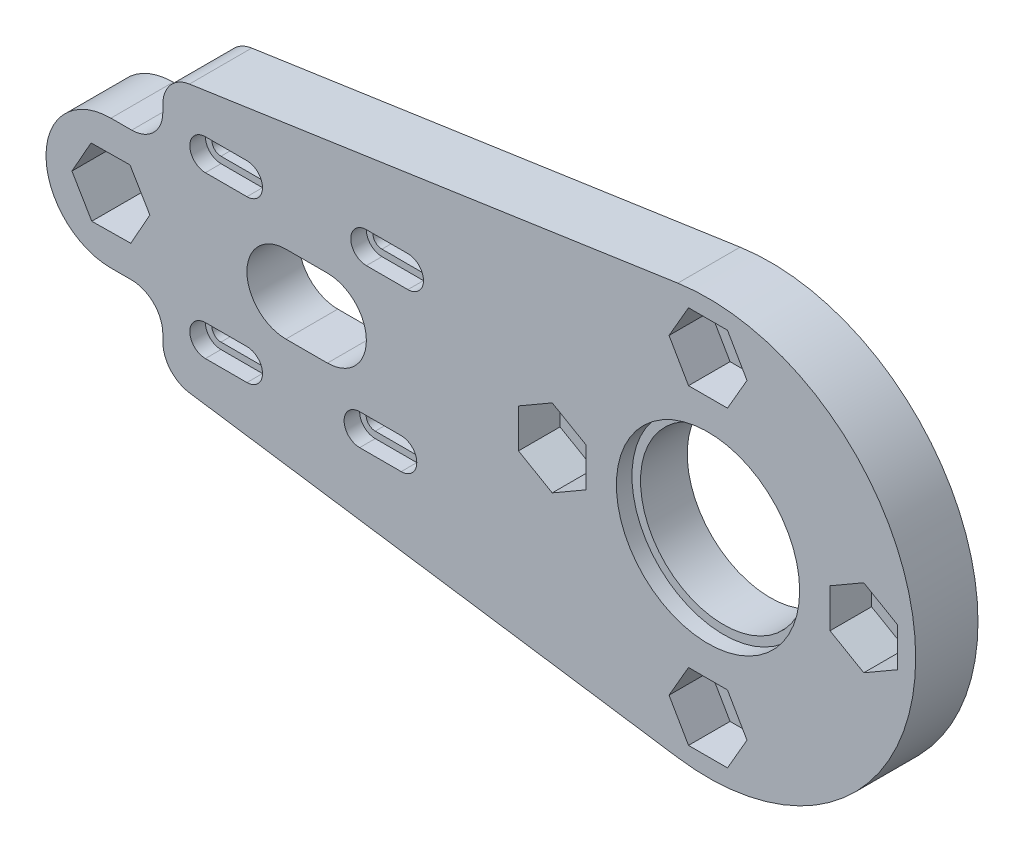
SolidWorks part; units mm, degrees
ref_plane "Front Plane" through (0, 0, 0) normal (0, 0, 1) x (1, 0, 0)
ref_plane "Top Plane" through (0, 0, 0) normal (0, 1, 0) x (1, 0, 0)
ref_plane "Right Plane" through (0, 0, 0) normal (1, 0, 0) x (0, 0, -1)
sketch "Sketch2" plane through (0, 0, 0) normal (0, 0, 1) x (1, 0, 0)
  line L1 (-105, -25) -> (-105, 25)
  line L2 (-105, 25) -> (-5.8155, 39.575)
  line L3 (-105, -25) -> (-5.8155, -39.575)
  circle A0 centre (0, 0) radius 10
  arc A1 (-5.8155, -39.575) -> (-5.8155, 39.575) centre (0, 0) ccw
  point P8 (-105, 0)
  dimension "D1" = 80
  dimension "D2" = 20
  dimension "D3" = 105
  dimension "D4" = 50
extrude "Boss-Extrude1" add sketch "Sketch2" along normal blind 12
sketch "Sketch3" plane through (0, 0, 12) normal (0, 0, 1) x (1, 0, 0)
  circle A0 centre (0, 0) radius 17.65
  dimension "D1" = 35.3
extrude "Cut-Extrude1" cut sketch "Sketch3" against normal blind 3
sketch "Sketch4" plane through (0, 0, 12) normal (0, 0, 1) x (1, 0, 0)
  line L6 (-73.3, 7.5) -> (-81.3, 7.5)
  line L8 (-73.3, -7.5) -> (-81.3, -7.5)
  arc A2 (-81.3, 7.5) -> (-81.3, -7.5) centre (-81.3, 0) ccw
  arc A3 (-73.3, -7.5) -> (-73.3, 7.5) centre (-73.3, 0) ccw
  point P7 (-77.3, 7.5)
  point P11 (-77.3, -7.5)
  dimension "D1" = 15
  dimension "D2" = 8
  dimension "D3" = 77.3
extrude "Cut-Extrude2" cut sketch "Sketch4" against normal through all and the other way through all
sketch "Sketch5" plane through (0, 0, 12) normal (0, 0, 1) x (1, 0, 0)
  circle A0 centre (30, 0) radius 3
  circle A1 centre (0, -30) radius 3
  circle A2 centre (-30, 0) radius 3
  circle A3 centre (0, 30) radius 3
  point P12 (0, 0)
  dimension "D2" = 6
  dimension "D1" = 30
  dimension "D3" = 4
extrude "Cut-Extrude3" cut sketch "Sketch5" against normal through all
sketch "Sketch6" plane through (0, 0, 9) normal (0, 0, 1) x (1, 0, 0)
  circle A0 centre (0, 0) radius 16
  dimension "D1" = 32
extrude "Cut-Extrude4" cut sketch "Sketch6" against normal through all
sketch "Sketch7" plane through (0, 0, 0) normal (0, 0, -1) x (-1, 0, 0)
  line L0 (73.3, 7.5) -> (81.3, -7.5) construction
  line L2 (51.8, -21.5) -> (102.8, -21.5)
  line L3 (51.8, -21.5) -> (51.8, 21.5)
  line L4 (51.8, 21.5) -> (102.8, 21.5)
  line L5 (102.8, -21.5) -> (102.8, 21.5)
  line L6 (51.8, -21.5) -> (102.8, 21.5) construction
  line L7 (51.8, 21.5) -> (102.8, -21.5) construction
  point P4 (77.3, 0)
  dimension "D1" = 51
  dimension "D2" = 43
extrude "Cut-Extrude5" cut sketch "Sketch7" against normal blind 2
chamfer "Chamfer1" distance 2 angle 45 4 edges at (-51.8, -21.5, 1) (-102.8, -21.5, 1) (-102.8, 21.5, 1) (-51.8, 21.5, 1)
sketch "Sketch8" plane through (0, 0, 12) normal (0, 0, 1) x (1, 0, 0)
  line L0 (30, -7.5056) -> (36.5, -3.7528)
  line L1 (7.5056, 30) -> (3.7528, 36.5)
  line L2 (3.7528, 36.5) -> (-3.7528, 36.5)
  line L3 (-3.7528, 36.5) -> (-7.5056, 30)
  line L4 (-7.5056, 30) -> (-3.7528, 23.5)
  line L5 (-3.7528, 23.5) -> (3.7528, 23.5)
  line L6 (3.7528, 23.5) -> (7.5056, 30)
  line L7 (36.5, -3.7528) -> (36.5, 3.7528)
  line L8 (36.5, 3.7528) -> (30, 7.5056)
  line L9 (30, 7.5056) -> (23.5, 3.7528)
  line L10 (23.5, 3.7528) -> (23.5, -3.7528)
  line L11 (23.5, -3.7528) -> (30, -7.5056)
  line L12 (-7.5056, -30) -> (-3.7528, -36.5)
  line L13 (-3.7528, -36.5) -> (3.7528, -36.5)
  line L14 (3.7528, -36.5) -> (7.5056, -30)
  line L15 (7.5056, -30) -> (3.7528, -23.5)
  line L16 (3.7528, -23.5) -> (-3.7528, -23.5)
  line L17 (-3.7528, -23.5) -> (-7.5056, -30)
  line L18 (-30, 7.5056) -> (-36.5, 3.7528)
  line L19 (-36.5, 3.7528) -> (-36.5, -3.7528)
  line L20 (-36.5, -3.7528) -> (-30, -7.5056)
  line L21 (-30, -7.5056) -> (-23.5, -3.7528)
  line L22 (-23.5, -3.7528) -> (-23.5, 3.7528)
  line L23 (-23.5, 3.7528) -> (-30, 7.5056)
  circle A0 centre (0, 30) radius 6.5 construction
  point P30 (0, 0)
  dimension "D1" = 13
  dimension "D2" = 4
extrude "Cut-Extrude6" cut sketch "Sketch8" against normal blind 8
sketch "Sketch9" plane through (0, 0, 12) normal (0, 0, 1) x (1, 0, 0)
  line L0 (-81.3, 7.5) -> (-73.3, -7.5) construction
  line L9 (-77.3, -15.5) -> (-77.3, 15.5) construction
  line L10 (-92.8, 0) -> (-61.8, 0) construction
  line L11 (-92.8, 15.5) -> (-63.0895, -15.5) construction
  line L12 (-92.8, -15.5) -> (-61.8, 15.5) construction
  line L13 (-96.8, 15.5) -> (-88.8, 15.5) construction
  line L14 (-65.8, 15.5) -> (-57.8, 15.5) construction
  line L15 (-67.0895, -15.5) -> (-59.0895, -15.5) construction
  line L16 (-96.8, -15.5) -> (-88.8, -15.5) construction
  line L17 (-65.8, 12.5) -> (-57.8, 12.5)
  line L18 (-88.8, 18.5) -> (-96.8, 18.5)
  line L19 (-96.8, 12.5) -> (-88.8, 12.5)
  line L20 (-65.8, 18.5) -> (-57.8, 18.5)
  line L23 (-59.0895, -12.5) -> (-67.0895, -12.5)
  line L24 (-67.0895, -18.5) -> (-59.0895, -18.5)
  line L25 (-88.8, -12.5) -> (-96.8, -12.5)
  line L26 (-96.8, -18.5) -> (-88.8, -18.5)
  arc A0 (-73.3, -7.5) -> (-73.3, 7.5) centre (-73.3, 0) ccw construction
  arc A1 (-57.8, 12.5) -> (-57.8, 18.5) centre (-57.8, 15.5) ccw
  arc A2 (-65.8, 18.5) -> (-65.8, 12.5) centre (-65.8, 15.5) ccw
  arc A3 (-88.8, 12.5) -> (-88.8, 18.5) centre (-88.8, 15.5) ccw
  arc A4 (-96.8, 18.5) -> (-96.8, 12.5) centre (-96.8, 15.5) ccw
  arc A5 (-96.8, -12.5) -> (-96.8, -18.5) centre (-96.8, -15.5) ccw
  arc A6 (-88.8, -18.5) -> (-88.8, -12.5) centre (-88.8, -15.5) ccw
  arc A7 (-67.0895, -12.5) -> (-67.0895, -18.5) centre (-67.0895, -15.5) ccw
  arc A8 (-59.0895, -18.5) -> (-59.0895, -12.5) centre (-59.0895, -15.5) ccw
  point P6 (-77.3, 0)
  point P10 (-77.3, 0)
  point P11 (-77.3, 0)
  point P14 (-77.3, 0)
  point P20 (-77.3, 0)
  point P23 (-92.8, 15.5)
  point P26 (-61.8, 15.5)
  point P29 (-63.0895, -15.5)
  point P32 (-92.8, -15.5)
  point P56 (-61.8, 15.5)
  point P57 (-92.8, 15.5)
  dimension "D8" = 6
  dimension "D9" = 6
  dimension "D10" = 6
  dimension "D11" = 6
  dimension "D12" = 6
  dimension "D13" = 6
  dimension "D14" = 6
  dimension "D15" = 6
  dimension "D1" = 31
  dimension "D2" = 31
  dimension "D3" = 31
  dimension "D4" = 8
  dimension "D5" = 8
  dimension "D6" = 8
  dimension "D7" = 8
extrude "Cut-Extrude7" cut sketch "Sketch9" against normal blind 3
sketch "Sketch10" plane through (0, 0, 9) normal (0, 0, 1) x (1, 0, 0)
  line L0 (-56.0895, -15.5) -> (-57.3395, -15.5) construction
  line L1 (-67.0895, -13.75) -> (-59.0895, -13.75)
  line L2 (-59.0895, -17.25) -> (-67.0895, -17.25)
  line L3 (-65.8, 15.5) -> (-57.8, 15.5) construction
  line L4 (-65.8, 17.25) -> (-57.8, 17.25)
  line L5 (-57.8, 13.75) -> (-65.8, 13.75)
  line L6 (-96.8, 17.25) -> (-88.8, 17.25)
  line L7 (-88.8, 13.75) -> (-96.8, 13.75)
  line L8 (-96.8, -13.75) -> (-88.8, -13.75)
  line L9 (-88.8, -17.25) -> (-96.8, -17.25)
  arc A0 (-96.8, -13.75) -> (-96.8, -17.25) centre (-96.8, -15.5) ccw
  arc A1 (-59.0895, -18.5) -> (-59.0895, -12.5) centre (-59.0895, -15.5) ccw construction
  arc A2 (-59.0895, -17.25) -> (-59.0895, -13.75) centre (-59.0895, -15.5) ccw
  arc A3 (-67.0895, -13.75) -> (-67.0895, -17.25) centre (-67.0895, -15.5) ccw
  arc A4 (-65.8, 17.25) -> (-65.8, 13.75) centre (-65.8, 15.5) ccw
  arc A5 (-57.8, 13.75) -> (-57.8, 17.25) centre (-57.8, 15.5) ccw
  arc A6 (-96.8, 17.25) -> (-96.8, 13.75) centre (-96.8, 15.5) ccw
  arc A7 (-88.8, 13.75) -> (-88.8, 17.25) centre (-88.8, 15.5) ccw
  arc A8 (-88.8, -17.25) -> (-88.8, -13.75) centre (-88.8, -15.5) ccw
  dimension "D2" = 3.5
  dimension "D3" = 3.5
  dimension "D4" = 3.5
  dimension "D5" = 3.5
  dimension "D6" = 3.5
  dimension "D7" = 3.5
  dimension "D8" = 3.5
  dimension "D9" = 3.5
  dimension "D1" = 1.25
extrude "Cut-Extrude8" cut sketch "Sketch10" against normal through all
sketch "Sketch11" plane through (0, 0, 12) normal (0, 0, 1) x (1, 0, 0)
  line L0 (-105, 25) -> (-105, -25) construction
  line L1 (-115, 12.5) -> (-105, 12.5)
  line L2 (-105, 12.5) -> (-105, -12.5)
  line L3 (-105, -12.5) -> (-115, -12.5)
  circle A0 centre (-115, 0) radius 3
  arc A1 (-115, 12.5) -> (-115, -12.5) centre (-115, 0) ccw
  dimension "D2" = 6
  dimension "D3" = 25
  dimension "D1" = 10
extrude "Boss-Extrude2" add sketch "Sketch11" against normal up to surface (12 mm away) up to face at (-77.3, 0, 0)
fillet "Fillet1" radius 6 4 edges at (-105, -25, 6) (-105, -12.5, 6) (-105, 25, 6) (-105, 12.5, 6)
sketch "Sketch12" plane through (0, 0, 12) normal (0, 0, 1) x (1, 0, 0)
  line L1 (-111.3173, 6.54) -> (-118.8225, 6.4593)
  line L2 (-118.8225, 6.4593) -> (-122.5051, -0.0807)
  line L3 (-122.5051, -0.0807) -> (-118.6827, -6.54)
  line L4 (-118.6827, -6.54) -> (-111.1775, -6.4593)
  line L5 (-111.1775, -6.4593) -> (-107.4949, 0.0807)
  line L6 (-107.4949, 0.0807) -> (-111.3173, 6.54)
  circle A0 centre (-115, 0) radius 6.5 construction
  dimension "D1" = 13
extrude "Cut-Extrude9" cut sketch "Sketch12" against normal blind 10
